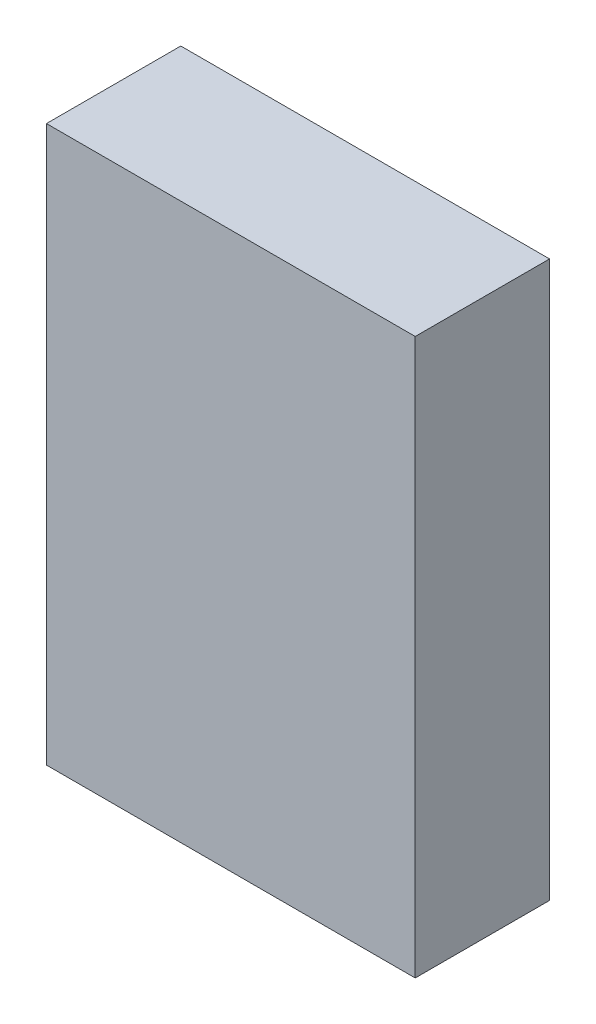
SolidWorks part; units mm, degrees
ref_plane "Alzado" through (0, 0, 0) normal (0, 0, 1) x (1, 0, 0)
ref_plane "Planta" through (0, 0, 0) normal (0, 1, 0) x (1, 0, 0)
ref_plane "Vista lateral" through (0, 0, 0) normal (1, 0, 0) x (0, 0, -1)
sketch "Croquis1" plane through (0, 0, 0) normal (0, 0, 1) x (1, 0, 0)
  line L1 (-64.6826, 44.8261) -> (-4.2826, 44.8261)
  line L2 (-64.6826, 44.8261) -> (-64.6826, -46.1739)
  line L3 (-64.6826, -46.1739) -> (-4.2826, -46.1739)
  line L4 (-4.2826, 44.8261) -> (-4.2826, -46.1739)
  dimension "D1" = 91
  dimension "D2" = 60.4
extrude "Saliente-Extruir1" add sketch "Croquis1" along normal blind 22
